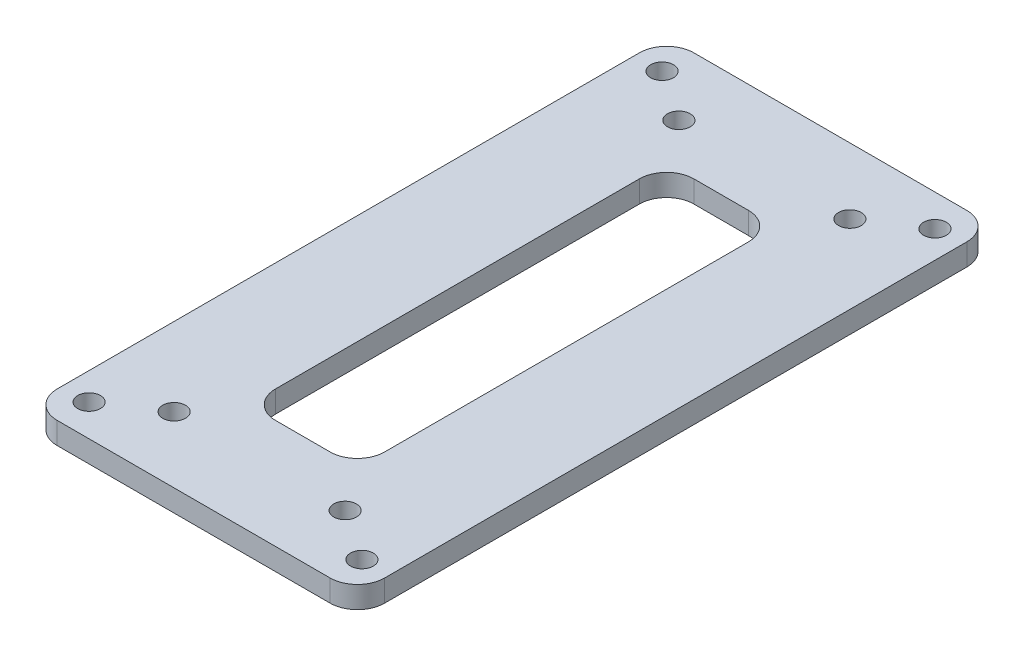
SolidWorks part; units mm, degrees
ref_plane "前视基准面" through (0, 0, 0) normal (0, 0, 1) x (1, 0, 0)
ref_plane "上视基准面" through (0, 0, 0) normal (0, 1, 0) x (1, 0, 0)
ref_plane "右视基准面" through (0, 0, 0) normal (1, 0, 0) x (0, 0, -1)
other "Configuration Table"
sketch "草图1" plane through (0, 0, 0) normal (0, 1, 0) x (1, 0, 0)
  line L0 (0, 46.8686) -> (0, -37.1951) construction
  line L1 (-18, -35) -> (18, -35)
  line L2 (-18, -35) -> (-18, 35)
  line L3 (-18, 35) -> (18, 35)
  line L4 (18, -35) -> (18, 35)
  line L5 (-18, -35) -> (18, 35) construction
  line L6 (-18, 35) -> (18, -35) construction
  line L7 (-32.226, 0) -> (32.7537, 0) construction
  line L8 (-6, -23) -> (-6, 23)
  line L9 (-6, 23) -> (6, 23)
  line L10 (6, -23) -> (6, 23)
  line L11 (-6, -23) -> (6, -23)
  circle A0 centre (-9.4, 27.75) radius 1.25
  circle A1 centre (9.4, 27.75) radius 1.25
  circle A2 centre (9.4, -27.75) radius 1.25
  circle A3 centre (-9.4, -27.75) radius 1.25
  circle A4 centre (-15, 31.5) radius 1.25
  circle A5 centre (15, 31.5) radius 1.25
  circle A6 centre (-15, -31.5) radius 1.25
  circle A7 centre (15, -31.5) radius 1.25
  point P0 (0, 0)
  dimension "D3" = 2.5
  dimension "D4" = 18.8
  dimension "D5" = 55.5
  dimension "D7" = 63
  dimension "D8" = 30
  dimension "D9" = 2.5
  dimension "D1" = 36
  dimension "D2" = 70
  dimension "D6" = 12
extrude "凸台-拉伸1" add sketch "草图1" along normal blind 2.4
fillet "圆角1" radius 3 8 edges at (-18, 1.2, -35) (18, 1.2, -35) (18, 1.2, 35) (-18, 1.2, 35) (-6, 1.2, 23) (6, 1.2, 23) (6, 1.2, -23) (-6, 1.2, -23)
